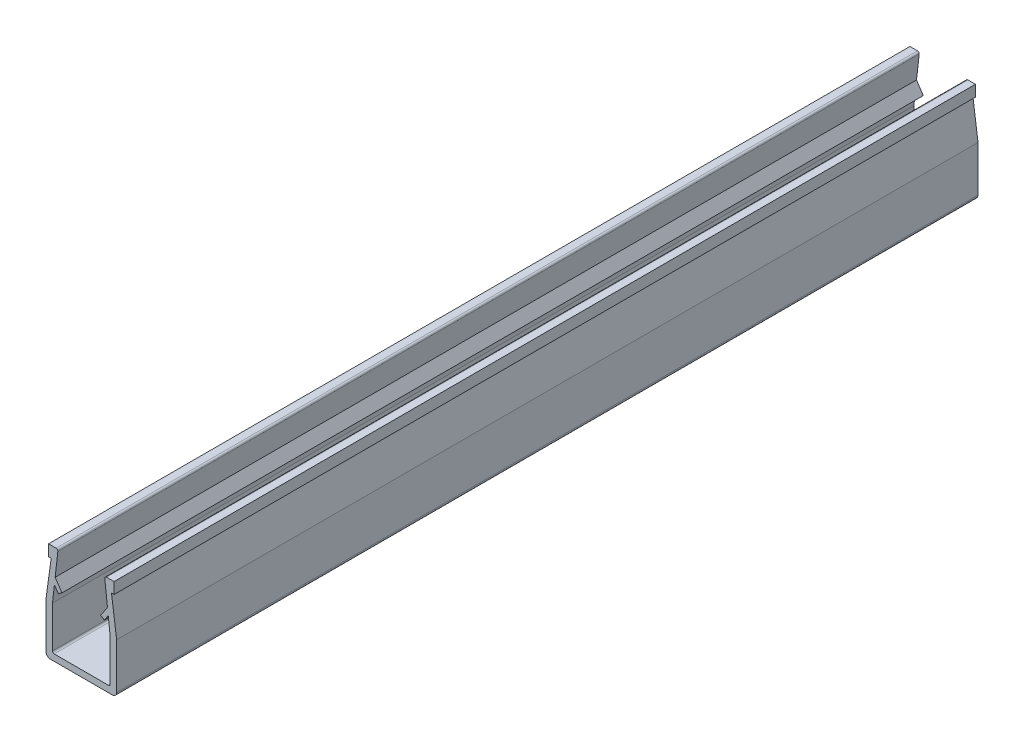
SolidWorks part; units mm, degrees
ref_plane "前视基准面" through (0, 0, 0) normal (0, 0, 1) x (1, 0, 0)
ref_plane "上视基准面" through (0, 0, 0) normal (0, 1, 0) x (1, 0, 0)
ref_plane "右视基准面" through (0, 0, 0) normal (1, 0, 0) x (0, 0, -1)
sketch "草图1" plane through (0, 0, 0) normal (0, 0, 1) x (1, 0, 0)
  line B0 (0, -1.3) -> (0, 0)
  line B1 (7.6, 0) -> (7.6, -1.3)
  line B2 (0, -1.3) -> (0.2983, -1.3)
  line B3 (7.3017, -1.3) -> (7.6, -1.3)
  line B4 (7.6, 0) -> (6.7239, 0)
  line B5 (6.5251, -0.2225) -> (6.8376, -2.9862)
  line B6 (6.9246, -3.7561) -> (7.15, -5.75)
  line B7 (7.15, -5.75) -> (7.15, -10.55)
  line B8 (6.95, -10.75) -> (0.65, -10.75)
  line B9 (0.45, -10.55) -> (0.45, -5.75)
  line B10 (0.45, -5.75) -> (0.6754, -3.7561)
  line B11 (0.7624, -2.9862) -> (1.0749, -0.2225)
  line B12 (0.8761, 0) -> (0, 0)
  line B13 (7.3017, -1.3) -> (7.9, -5.7077)
  line B14 (7.9, -5.7077) -> (7.9, -11)
  line B15 (7.4, -11.5) -> (0.2, -11.5)
  line B16 (-0.3, -11) -> (-0.3, -5.7077)
  line B17 (-0.3, -5.7077) -> (0.2983, -1.3)
  line B18 (0.7624, -2.9862) -> (1.55, -4.1653)
  line B19 (0.6754, -3.7561) -> (1.1342, -4.443)
  line B20 (1.55, -4.1653) -> (1.1342, -4.443)
  line B21 (6.8376, -2.9862) -> (6.05, -4.1653)
  line B22 (6.9246, -3.7561) -> (6.4658, -4.443)
  line B23 (6.05, -4.1653) -> (6.4658, -4.443)
  arc B24 (6.7239, 0) -> (6.5251, -0.2225) centre (6.7239, -0.2) ccw
  arc B25 (6.95, -10.75) -> (7.15, -10.55) centre (6.95, -10.55) ccw
  arc B26 (0.45, -10.55) -> (0.65, -10.75) centre (0.65, -10.55) ccw
  arc B27 (1.0749, -0.2225) -> (0.8761, 0) centre (0.8761, -0.2) ccw
  arc B28 (7.4, -11.5) -> (7.9, -11) centre (7.4, -11) ccw
  arc B29 (-0.3, -11) -> (0.2, -11.5) centre (0.2, -11) ccw
sketch_block_instance "A$C3E8E6528-1"
sketch_block "A$C3E8E6528"
extrude "凸台-拉伸1" add sketch "草图1" along normal blind 100
